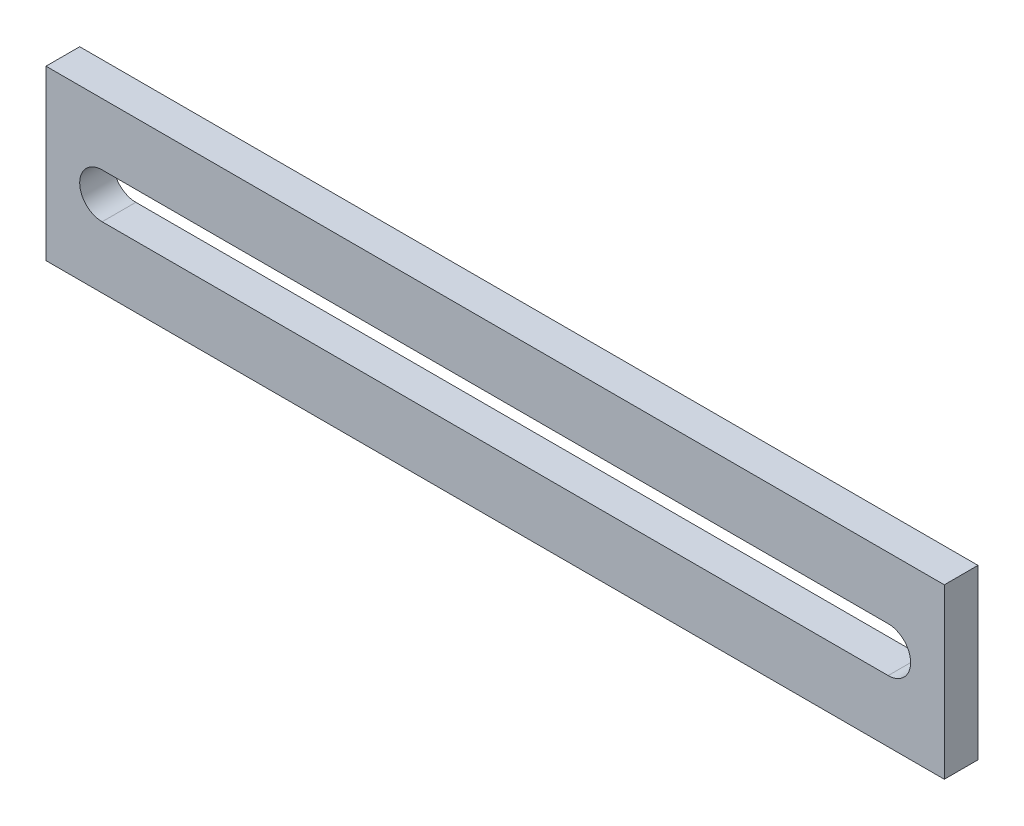
SolidWorks part; units mm, degrees
ref_plane "Front Plane" through (0, 0, 0) normal (0, 0, 1) x (1, 0, 0)
ref_plane "Top Plane" through (0, 0, 0) normal (0, 1, 0) x (1, 0, 0)
ref_plane "Right Plane" through (0, 0, 0) normal (1, 0, 0) x (0, 0, -1)
sketch "Sketch1" plane through (0, 0, 0) normal (0, 0, 1) x (1, 0, 0)
  line L1 (-40, 7.5) -> (40, 7.5)
  line L2 (-40, 7.5) -> (-40, -7.5)
  line L3 (-40, -7.5) -> (40, -7.5)
  line L4 (40, 7.5) -> (40, -7.5)
  line L5 (-40, 7.5) -> (40, -7.5) construction
  line L6 (-40, -7.5) -> (40, 7.5) construction
  point P0 (0, 0)
  dimension "D1" = 15
  dimension "D2" = 80
extrude "Boss-Extrude1" add sketch "Sketch1" along normal blind 3
sketch "Sketch2" plane through (0, 0, 3) normal (0, 0, 1) x (1, 0, 0)
  line L0 (-35, 0) -> (35, 0) construction
  line L1 (-35, 2) -> (35, 2)
  line L2 (-35, -2) -> (35, -2)
  line L3 (-40, 7.5) -> (-40, -7.5) construction
  line L4 (40, -7.5) -> (40, 7.5) construction
  arc A0 (-35, 2) -> (-35, -2) centre (-35, 0) ccw
  arc A1 (35, -2) -> (35, 2) centre (35, 0) ccw
  point P3 (0, 0)
  dimension "D1" = 2
  dimension "D2" = 5
  dimension "D3" = 5
extrude "Cut-Extrude1" cut sketch "Sketch2" against normal blind 3
